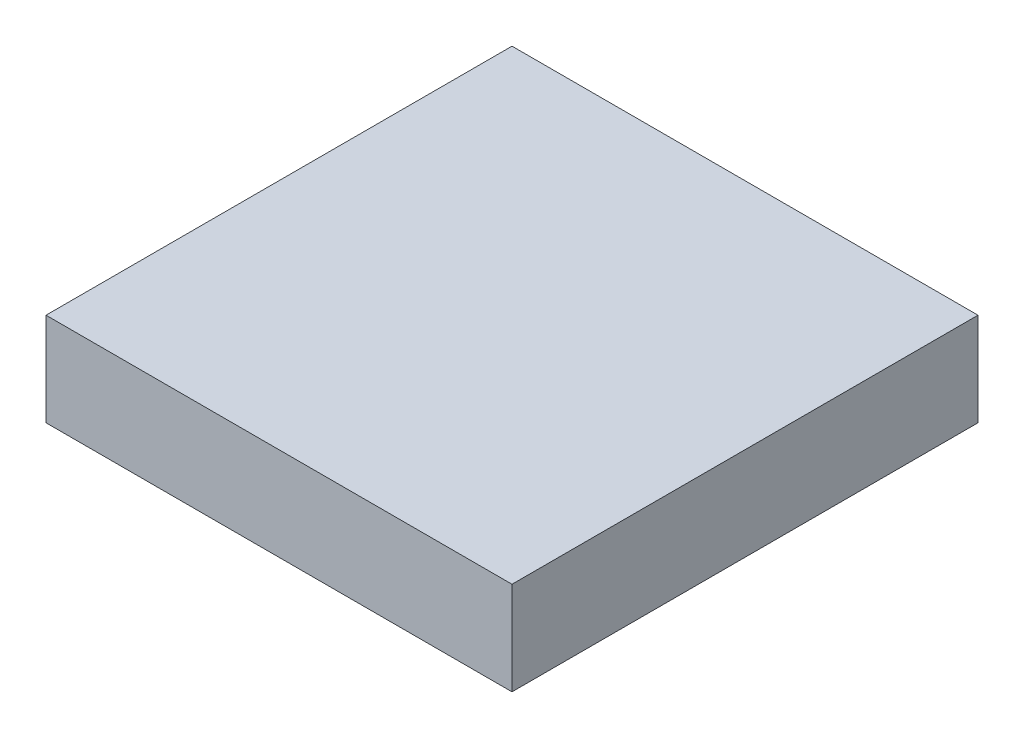
SolidWorks part; units mm, degrees
material "ABS PC"
ref_plane "Front Plane" through (0, 0, 0) normal (0, 0, 1) x (1, 0, 0)
ref_plane "Top Plane" through (0, 0, 0) normal (0, 1, 0) x (1, 0, 0)
ref_plane "Right Plane" through (0, 0, 0) normal (1, 0, 0) x (0, 0, -1)
sketch "Sketch1" plane through (0, 0, 0) normal (0, 1, 0) x (1, 0, 0)
  line L1 (-6.35, -6.35) -> (6.35, -6.35)
  line L2 (-6.35, -6.35) -> (-6.35, 6.35)
  line L3 (-6.35, 6.35) -> (6.35, 6.35)
  line L4 (6.35, -6.35) -> (6.35, 6.35)
  line L5 (-6.35, -6.35) -> (6.35, 6.35) construction
  line L6 (-6.35, 6.35) -> (6.35, -6.35) construction
  point P0 (0, 0)
  dimension "D1" = 12.7
  dimension "D2" = 12.7
extrude "Boss-Extrude1" add sketch "Sketch1" along normal blind 2.54
